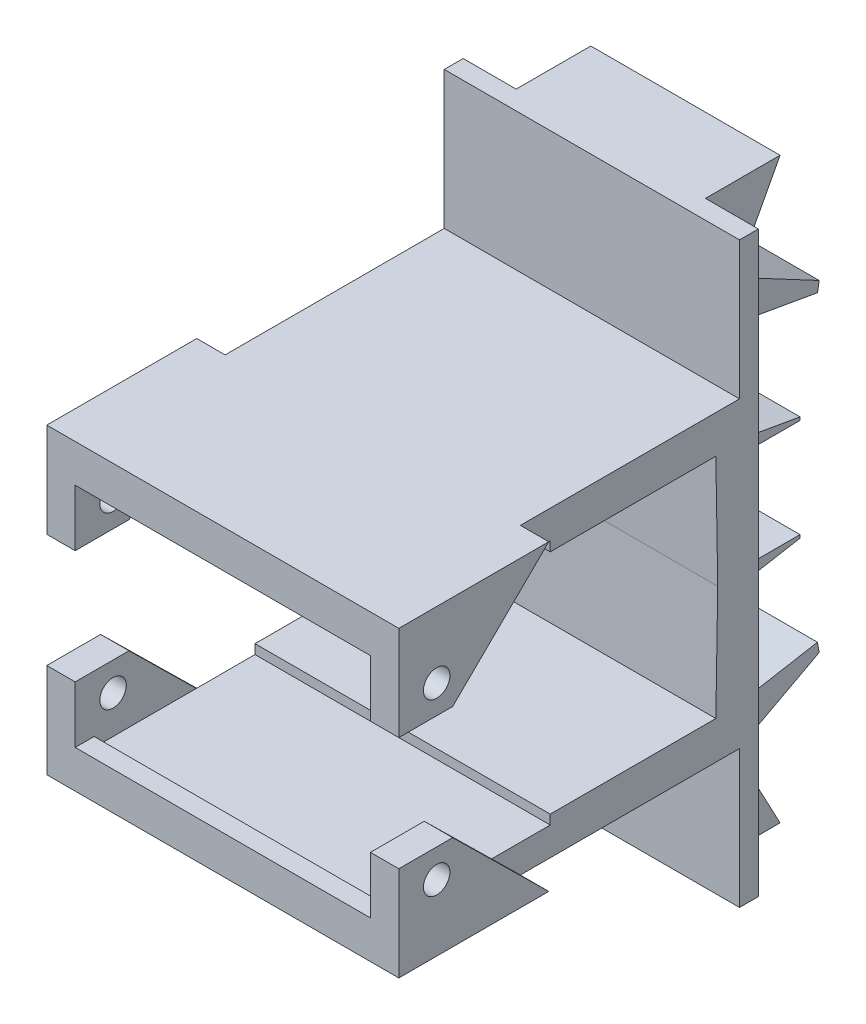
SolidWorks part; units mm, degrees
ref_plane "前视基准面" through (0, 0, 0) normal (0, 0, 1) x (1, 0, 0)
ref_plane "上视基准面" through (0, 0, 0) normal (0, 1, 0) x (1, 0, 0)
ref_plane "右视基准面" through (0, 0, 0) normal (1, 0, 0) x (0, 0, -1)
sketch "草图1" plane through (0, 0, 0) normal (0, 0, 1) x (1, 0, 0)
  line L0 (-15.6, 12) -> (15.6, 12)
  line L3 (-15.6, -12) -> (15.6, -12)
  line L4 (15.6, 12) -> (15.6, -12)
  line L5 (-15.6, 12) -> (-15.6, -12)
extrude "凸台-拉伸1" add sketch "草图1" along normal blind 2 and the other way blind 1
sketch "草图2" plane through (0, 0, 2) normal (0, 0, 1) x (1, 0, 0)
  line L1 (15.6, 12) -> (-15.6, 12)
  line L2 (15.6, 12) -> (15.6, 16)
  line L3 (15.6, 16) -> (-15.6, 16)
  line L4 (-15.6, 12) -> (-15.6, 16)
  line L5 (15.6, -16) -> (-15.6, -16)
  line L6 (-15.6, -12) -> (-15.6, -16)
  line L7 (15.6, -12) -> (-15.6, -12)
  line L8 (15.6, -12) -> (15.6, -16)
  dimension "D1" = 4
extrude "凸台-拉伸2" add sketch "草图2" along normal blind 36 and the other way blind 3
sketch "草图3" plane through (-15.6, 0, 0) normal (-1, 0, 0) x (0, 0, 1)
  line L0 (2, 12) -> (2, -12) construction
  line L1 (2, 12) -> (38, 12) construction
  line L3 (38, 16) -> (31, 16)
  line L4 (38, 16) -> (38, 6)
  line L5 (38, 6) -> (32.3107, 6)
  line L7 (32.3107, 6) -> (22.1529, 16)
  line L8 (-1, 16) -> (38, 16) construction
  line L9 (22.1529, 16) -> (31, 16)
  line L13 (38, -16) -> (38, -6)
  line L14 (38, -16) -> (31, -16)
  line L15 (22.1529, -16) -> (31, -16)
  line L16 (32.3107, -6) -> (22.1529, -16)
  line L17 (38, -6) -> (32.3107, -6)
  circle A0 centre (34, 9) radius 1.4
  circle A1 centre (34, -9) radius 1.4
  dimension "D1" = 32
  dimension "D2" = 3
  dimension "D3" = 10
  dimension "D4" = 7
extrude "凸台-拉伸3" add sketch "草图3" along normal blind 3
sketch "草图4" plane through (0, 0, -1) normal (0, 0, -1) x (-1, 0, 0)
  line L0 (15.6, -12) -> (15.6, -16) construction
  line L1 (15.6, -16) -> (-15.6, -16) construction
  circle A0 centre (13.6, -14) radius 1.4
  circle A1 centre (13.6, 14) radius 1.4
  circle A2 centre (-13.6, -14) radius 1.4
  circle A3 centre (-13.6, 14) radius 1.4
  dimension "D1" = 2
  dimension "D2" = 2
extrude "切除-拉伸1" cut sketch "草图4" against normal blind 8
mirror "镜向1" about plane through (0, 0, 0) normal (1, 0, 0) of "凸台-拉伸3"
sketch "草图5" plane through (-15.6, 0, 0) normal (-1, 0, 0) x (0, 0, 1)
  line L0 (2, 12) -> (26.216, 12) construction
  line L1 (19, 12) -> (36, 12)
  line L2 (19, 12) -> (19, 13)
  line L3 (19, 13) -> (36, 13)
  line L4 (36, 12) -> (36, 13)
  line L5 (2, 12) -> (2, -12) construction
  line L7 (19, -12) -> (19, -13)
  line L8 (19, -12) -> (36, -12)
  line L9 (19, -13) -> (36, -13)
  line L10 (36, -12) -> (36, -13)
  dimension "D1" = 17
  dimension "D2" = 34
  dimension "D3" = 1
extrude "切除-拉伸2" cut sketch "草图5" against normal blind 31.2
sketch "草图6" plane through (-15.6, 0, 0) normal (-1, 0, 0) x (0, 0, 1)
  line L0 (3.0082, 0) -> (2, 0)
  line L1 (2, 12) -> (1.5, 12)
  line L2 (2, 12) -> (2, -12)
  line L3 (2, -12) -> (1.5, -12)
  line L6 (1.3, 0) -> (1.5, 12)
  line L7 (1.3, 0) -> (1.5, -12)
  line M17 (2, -12) -> (2, 12)
  dimension "D1" = 0.5
extrude "切除-拉伸3" cut sketch "草图6" against normal blind 31.2 contours L6 L7 L3 L1 M17
sketch "草图7" plane through (0, 0, -1) normal (0, 0, -1) x (-1, 0, 0)
  line L2 (-15.6, -16) -> (-15.6, 16)
  line L4 (15.6, -16) -> (15.6, 16)
  line L6 (-15.6, -16) -> (-15.6, -36)
  line L7 (-15.6, -36) -> (15.6, -36)
  line L8 (15.6, -16) -> (15.6, -36)
  line L9 (-15.6, 36) -> (15.6, 36)
  line L14 (15.6, 16) -> (15.6, 36)
  line L16 (-15.6, 16) -> (-15.6, 36)
  circle A0 centre (-13.6, -14) radius 1.4
  circle A1 centre (-13.6, 14) radius 1.4
  circle A2 centre (13.6, 14) radius 1.4
  circle A3 centre (13.6, -14) radius 1.4
  dimension "D1" = 20
extrude "凸台-拉伸4" add sketch "草图7" along normal blind 2
sketch "草图8" plane through (0, 0, 0) normal (1, 0, 0) x (0, 0, -1)
  line L0 (13, 0) -> (18.2385, 0)
  line L6 (13, 5.2239) -> (13, 5.5524)
  line L7 (13, 5.5524) -> (3.1519, 7.2889)
  line L8 (3, 5.2239) -> (3, 30.5482)
  line L9 (3.1519, 7.2889) -> (13, 5.5524)
  line L10 (3.1519, 7.2889) -> (4.9926, 17.7279)
  line L12 (4.9926, 17.7279) -> (14.8407, 15.9914)
  line L13 (14.8407, 15.9914) -> (15.0228, 17.0241)
  line L19 (15.0228, 17.0241) -> (6.1933, 21.7188)
  line L20 (3, 5.2239) -> (13, 5.2239)
  line L21 (15.0228, 17.0241) -> (6.1933, 21.7188)
  line L23 (6.1933, 21.7188) -> (10.888, 30.5482)
  line L25 (10.888, 30.5482) -> (3, 30.5482)
  line L26 (3, -5.2239) -> (13, -5.2239)
  line L27 (13, -5.2239) -> (13, -5.5524)
  line L28 (13, -5.5524) -> (3.1519, -7.2889)
  line L29 (3.1519, -7.2889) -> (4.9926, -17.7279)
  line L30 (14.8407, -15.9914) -> (15.0228, -17.0241)
  line L31 (4.9926, -17.7279) -> (14.8407, -15.9914)
  line L32 (15.0228, -17.0241) -> (6.1933, -21.7188)
  line L33 (6.1933, -21.7188) -> (10.888, -30.5482)
  line L34 (3, -5.2239) -> (3, -30.5482)
  line L35 (10.888, -30.5482) -> (3, -30.5482)
  dimension "D2" = 10
  dimension "D3" = 10
  dimension "D4" = 10
  dimension "D5" = 10.6
  dimension "D6" = 18
extrude "凸台-拉伸5" add sketch "草图8" along normal blind 10 and the other way blind 10 contours L23 L25 L8 L20 L6 L7 L10 L12 L13 L19 | L35 L33 L32 L30 L31 L29 L28 L27 L26 L34
sketch "草图9" plane through (0, 0, -3) normal (0, 0, -1) x (-1, 0, 0)
  line L1 (15.6, 36) -> (-10, 36)
  line L2 (15.6, 36) -> (15.6, 30.5482)
  line L3 (15.6, 30.5482) -> (-10, 30.5482)
  line L5 (-10, 30.5482) -> (-15.6, 30.5482)
  line L7 (-10, 36) -> (-15.6, 36)
  line L8 (-15.6, 30.5482) -> (-15.6, 36)
  line L9 (15.6, -36) -> (-10, -36)
  line L10 (15.6, -36) -> (15.6, -30.5482)
  line L11 (15.6, -30.5482) -> (-10, -30.5482)
  line L13 (-10, -30.5482) -> (-15.6, -30.5482)
  line L15 (-10, -36) -> (-15.6, -36)
  line L16 (-15.6, -30.5482) -> (-15.6, -36)
extrude "切除-拉伸4" cut sketch "草图9" against normal blind 10
